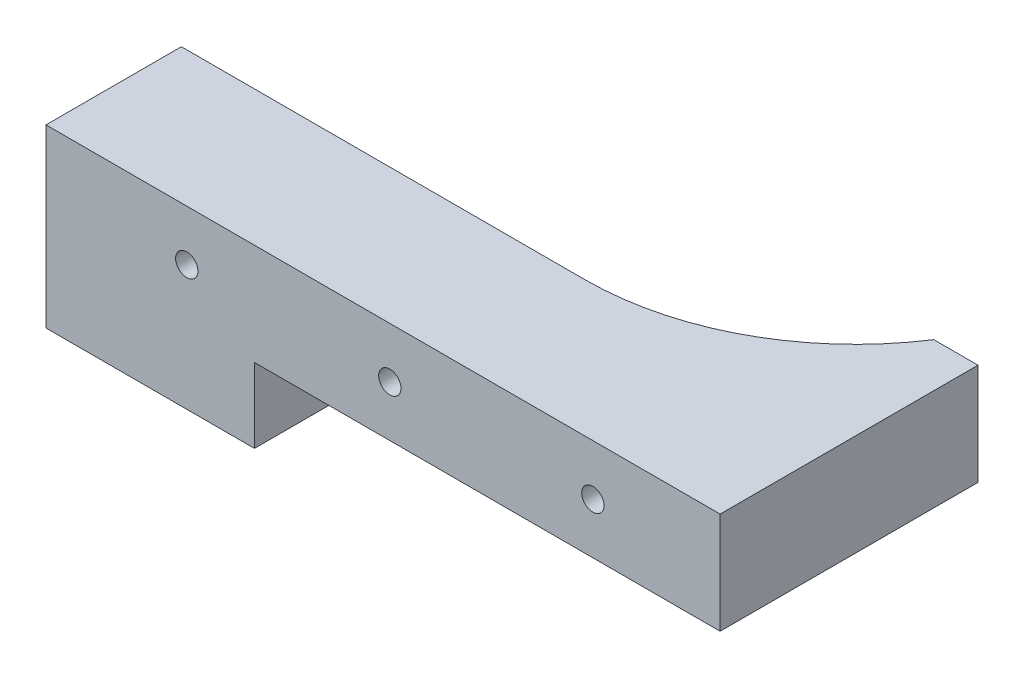
SolidWorks part; units mm, degrees
ref_plane "Front Plane" through (0, 0, 0) normal (0, 0, 1) x (1, 0, 0)
ref_plane "Top Plane" through (0, 0, 0) normal (0, 1, 0) x (1, 0, 0)
ref_plane "Right Plane" through (0, 0, 0) normal (1, 0, 0) x (0, 0, -1)
sketch "Sketch1" plane through (0, 0, 0) normal (0, 0, 1) x (1, 0, 0)
  line L0 (-137.6995, 269.2927) -> (-137.6995, -50) construction
  line L1 (-106.9, 1) -> (-106.9, 12) construction
  line L2 (-106.9, 12) -> (-7.9096, 12) construction
  line L3 (-137.6995, 269.2927) -> (-137.6995, -50)
  line L4 (-106.9, 1) -> (-106.9, 12)
  line L5 (-106.9, 12) -> (-7.9096, 12)
  line L6 (-7.9096, 12) -> (-7.9096, 27)
  line L7 (-7.9096, 27) -> (-137.6995, 27)
  line L8 (-106.9, 1) -> (-137.6995, 1)
  circle A0 centre (-116.9, 19.5) radius 1.65
  circle A1 centre (-86.9, 19.5) radius 1.65
  circle A2 centre (-56.9, 19.5) radius 1.65
  circle A3 centre (-26.9, 19.5) radius 1.65
  dimension "D1" = 4
extrude "Boss-Extrude1" add sketch "Sketch1" against normal up to surface (38.1 mm away) contours L8 L4 L5 L6 L7 L3 A2 A1 A0
sketch "Sketch3" plane through (-137.6995, 0, 0) normal (-1, 0, 0) x (0, 0, 1)
  circle A0 centre (-10.6985, 14) radius 1.65
extrude "Cut-Extrude1" cut sketch "Sketch3" against normal blind 20
sketch "Sketch4" plane through (0, 27, 0) normal (0, 1, 0) x (1, 0, 0)
  line L0 (-38.1, 28.0463) -> (-38.1, 32.7735) construction
  line L1 (-38.1, 28.0463) -> (-38.1, 32.7735)
  line L2 (-38.1, 32.7735) -> (-38.1, 38.1)
  line L3 (-38.1, 28.0463) -> (-38.1, 0)
  line L4 (-106.9, 20) -> (-137.6995, 20)
  line L5 (-44.6278, 38.1) -> (-137.6995, 38.1)
  line L8 (-7.9096, 38.1) -> (-137.6995, 38.1)
  line L9 (-137.6995, 38.1) -> (-137.6995, 0)
  line L10 (-137.6995, 0) -> (-7.9096, 0)
  line L11 (-7.9096, 0) -> (-7.9096, 38.1)
  line L12 (-7.9096, 205.6245) -> (-7.9096, 250.0267)
  line L13 (-7.9096, 250.0267) -> (-13.5089, 250.0267)
  line L14 (-13.5089, 250.0267) -> (-13.5089, 325.0267)
  line L15 (-13.5089, 325.0267) -> (-38.1, 325.0267)
  line L16 (-38.1, 325.0267) -> (-38.1, 60)
  line L17 (-78.1, 20) -> (-106.9, 20)
  line L18 (-106.9, 20) -> (-106.9, 0)
  line L19 (-106.9, 0) -> (-7.9096, 0)
  line L20 (-7.9096, 0) -> (-7.9096, 171.429)
  line L21 (-7.9096, 179.6245) -> (-7.9096, 197.429)
  line L27 (-78.1, 20) -> (-106.9, 20)
  line L32 (-7.9096, 38.1) -> (-38.1, 38.1)
  line L33 (-137.6995, 38.1) -> (-137.6995, 0)
  line L34 (-38.1, 0) -> (-7.9096, 0)
  line L35 (-7.9096, 0) -> (-7.9096, 38.1)
  arc A3 (-7.9096, 205.6245) -> (-7.9096, 197.429) centre (-6.05, 201.5267) ccw
  arc A4 (-78.1, 20) -> (-38.1, 60) centre (-78.1, 60) ccw
  arc A5 (-7.9096, 179.6245) -> (-7.9096, 171.429) centre (-6.05, 175.5267) ccw
  arc A6 (-7.9096, 205.6245) -> (-7.9096, 197.429) centre (-6.05, 201.5267) ccw
  arc A7 (-78.1, 20) -> (-44.6278, 38.1) centre (-78.1, 60) ccw
  arc A8 (-7.9096, 179.6245) -> (-7.9096, 171.429) centre (-6.05, 175.5267) ccw
  line M18 (-7.9096, 38.1) -> (-137.6995, 38.1)
  line M19 (-137.6995, 38.1) -> (-137.6995, 0)
  line M20 (-137.6995, 0) -> (-7.9096, 0)
  line M21 (-7.9096, 0) -> (-7.9096, 38.1)
  dimension "D2" = 0
  dimension "D1" = 0
extrude "Cut-Extrude3" cut sketch "Sketch4" against normal through all and the other way through all contours L27 A7 L4 M18 M19 | L1 L3 L2 M20 M21 M18
